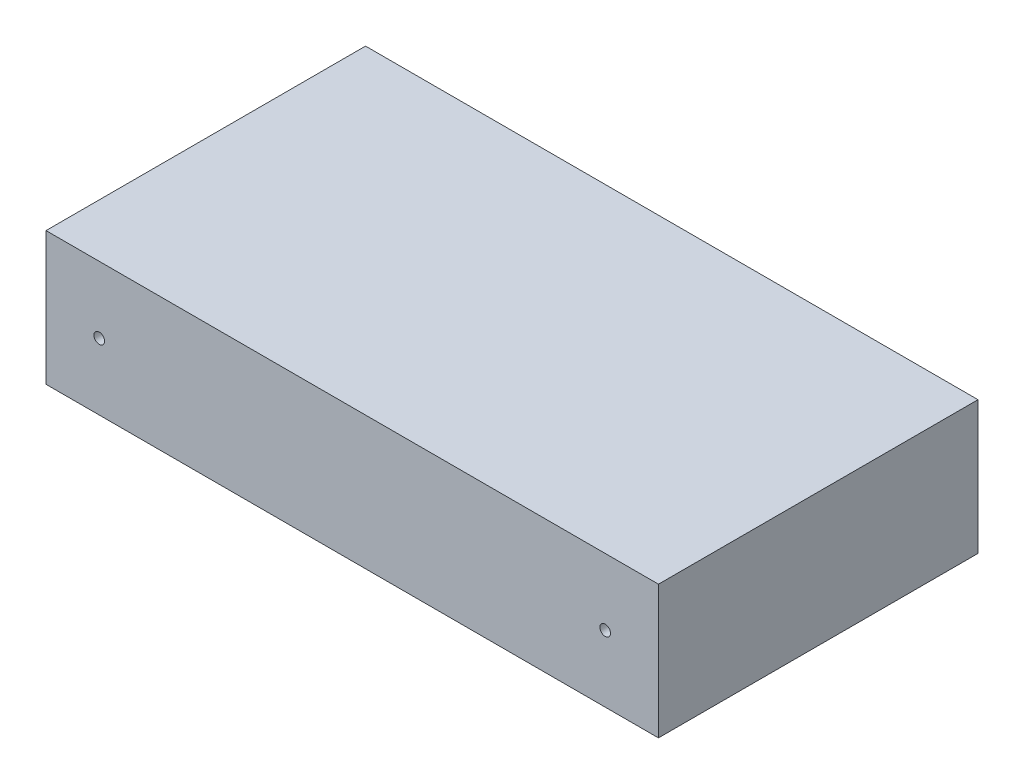
SolidWorks part; units mm, degrees
ref_plane "Front Plane" through (0, 0, 0) normal (0, 0, 1) x (1, 0, 0)
ref_plane "Top Plane" through (0, 0, 0) normal (0, 1, 0) x (1, 0, 0)
ref_plane "Right Plane" through (0, 0, 0) normal (1, 0, 0) x (0, 0, -1)
sketch "Sketch1" plane through (0, 0, 0) normal (0, 1, 0) x (1, 0, 0)
  line L1 (0, 0) -> (230, 0)
  line L2 (0, 0) -> (0, 120)
  line L3 (0, 120) -> (230, 120)
  line L4 (230, 0) -> (230, 120)
  dimension "D1" = 120
  dimension "D2" = 230
extrude "Boss-Extrude1" add sketch "Sketch1" along normal blind 50
sketch "Sketch2" plane through (0, 0, 0) normal (0, 0, 1) x (1, 0, 0)
  line L0 (0, 50) -> (0, 0) construction
  line L1 (230, 50) -> (230, 0) construction
  circle A0 centre (20, 25) radius 2
  circle A1 centre (210, 25) radius 2
  dimension "D3" = 4
  dimension "D4" = 4
  dimension "D1" = 20
  dimension "D2" = 20
extrude "Cut-Extrude1" cut sketch "Sketch2" against normal blind 10
